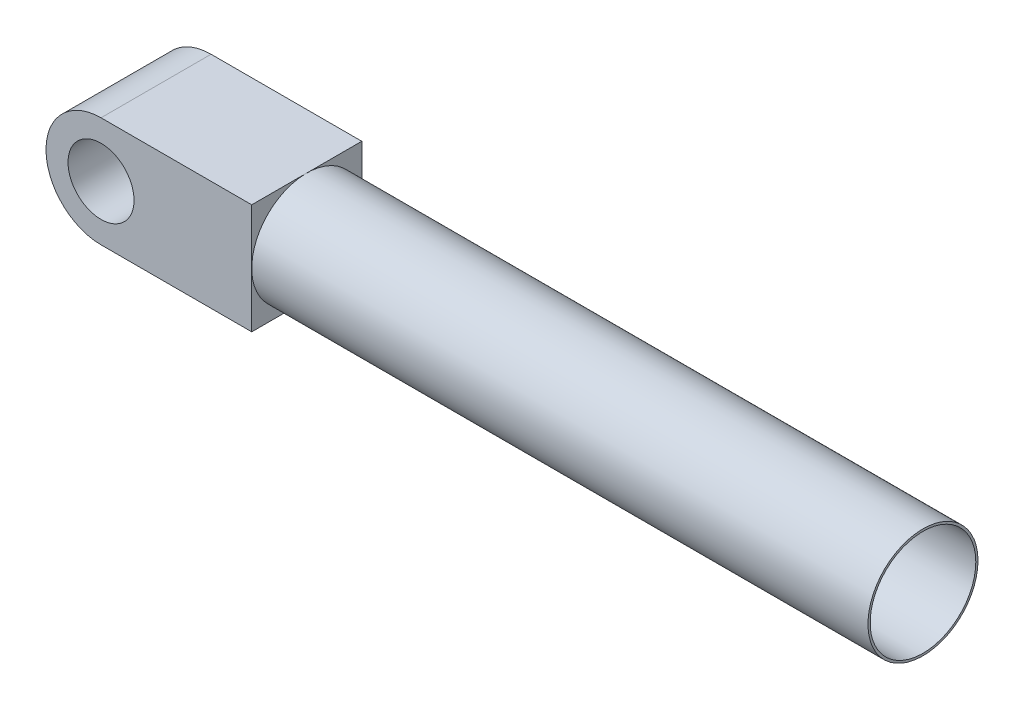
SolidWorks part; units mm, degrees
ref_plane "前视基准面" through (0, 0, 0) normal (0, 0, 1) x (1, 0, 0)
ref_plane "上视基准面" through (0, 0, 0) normal (0, 1, 0) x (1, 0, 0)
ref_plane "右视基准面" through (0, 0, 0) normal (1, 0, 0) x (0, 0, -1)
sketch "草图1" plane through (0, 0, 0) normal (0, 0, 1) x (1, 0, 0)
  line L0 (0, 25) -> (68.4825, 25)
  line L1 (68.4825, 25) -> (68.4825, -25)
  line L2 (68.4825, -25) -> (0, -25)
  circle A0 centre (0, 0) radius 15
  arc A1 (0, 25) -> (0, -25) centre (0, 0) ccw
  dimension "D1" = 30
  dimension "D2" = 50
extrude "凸台-拉伸1" add sketch "草图1" along normal mid plane 50
sketch "草图2" plane through (68.4825, 0, 0) normal (1, 0, 0) x (0, 0, -1)
  circle A0 centre (0, 0) radius 24
  circle A1 centre (0, 0) radius 25
  dimension "D1" = 48
  dimension "D2" = 50
extrude "凸台-拉伸2" add sketch "草图2" along normal blind 280 separate body
scale "缩放比例1" bodies to scale 106 107 scale about origin uniform scaling yes scale factor 0.6
